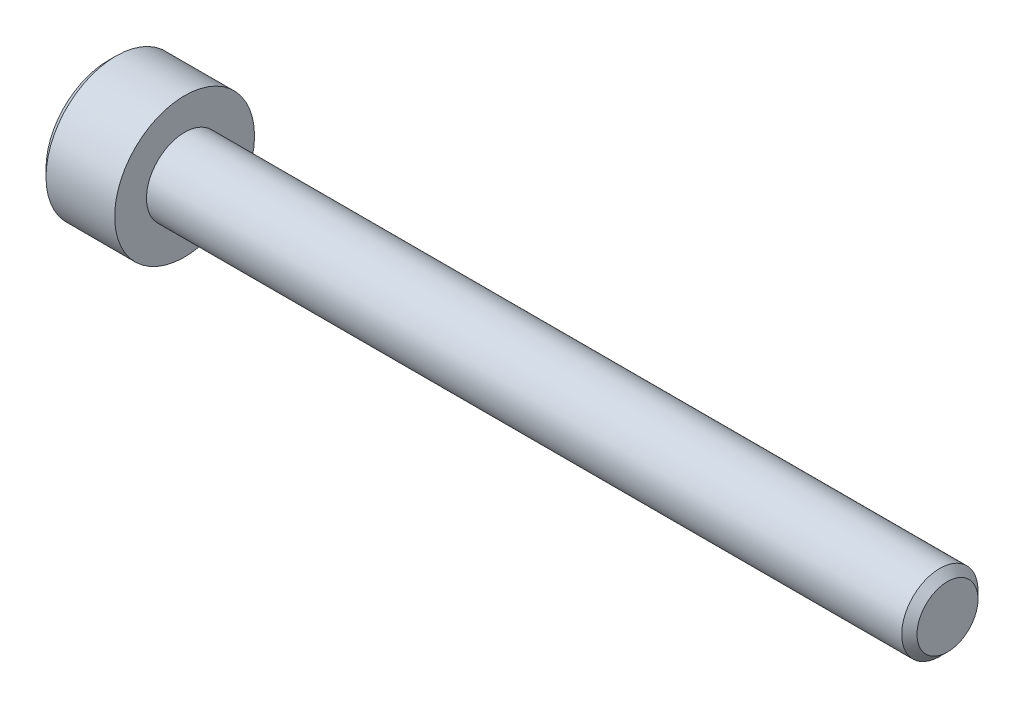
SolidWorks part; units mm, degrees
ref_plane "Front Plane" through (0, 0, 0) normal (0, 0, 1) x (1, 0, 0)
ref_plane "Top Plane" through (0, 0, 0) normal (0, 1, 0) x (1, 0, 0)
ref_plane "Right Plane" through (0, 0, 0) normal (1, 0, 0) x (0, 0, -1)
sketch "Sketch1" plane through (0, 0, 0) normal (0, 0, 1) x (1, 0, 0)
  line L0 (-3, 2.75) -> (-3, 0)
  line L1 (-3, 0) -> (0, 0)
  line L2 (0, 0) -> (0, 2.75)
  line L3 (0, 2.75) -> (-3, 2.75)
  line L4 (-3, 0) -> (0, 0) construction
revolve "Revolve1" add sketch "Sketch1" angle 360 about L4
sketch "Sketch2" plane through (0, 0, 0) normal (1, 0, 0) x (0, 0, -1)
  circle A0 centre (0, 0) radius 1.5
extrude "Boss-Extrude1" add sketch "Sketch2" along normal blind 30
sketch "Sketch3" plane through (-3, 0, 0) normal (-1, 0, 0) x (0, 0, 1)
  line L0 (1.25, -0.7217) -> (1.25, 0.7217)
  line L1 (1.25, 0.7217) -> (0, 1.4434)
  line L2 (0, 1.4434) -> (-1.25, 0.7217)
  line L3 (-1.25, 0.7217) -> (-1.25, -0.7217)
  line L4 (-1.25, -0.7217) -> (0, -1.4434)
  line L5 (0, -1.4434) -> (1.25, -0.7217)
extrude "Cut-Extrude1" cut sketch "Sketch3" against normal blind 1.5
sketch "Sketch4" plane through (0, 0, 0) normal (0, 0, 1) x (1, 0, 0)
  line L0 (-1.5, 1.25) -> (-1.5, 0)
  line L1 (-1.5, 0) -> (-1.1651, 0)
  line L2 (-1.1651, 0) -> (-1.5, 1.25)
  line L3 (-1.5, 0) -> (-1.165, 0) construction
revolve "Cut-Revolve1" cut sketch "Sketch4" angle 360 about L3
chamfer "Chamfer1" distance 0.3 angle 45 2 edges at (30, 0, -1.5) (-3, 0, -2.75)
